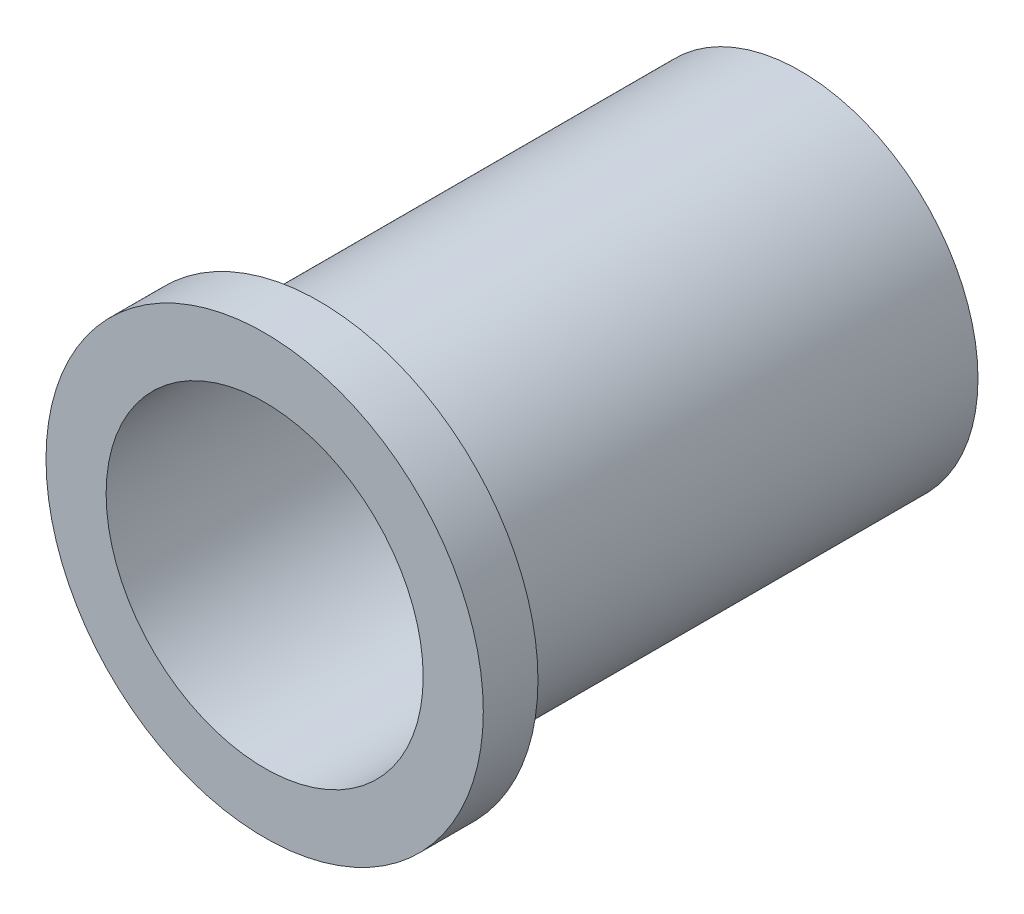
SolidWorks part; units mm, degrees
ref_plane "Front Plane" through (0, 0, 0) normal (0, 0, 1) x (1, 0, 0)
ref_plane "Top Plane" through (0, 0, 0) normal (0, 1, 0) x (1, 0, 0)
ref_plane "Right Plane" through (0, 0, 0) normal (1, 0, 0) x (0, 0, -1)
ref_plane "Plane1" through (0, 14.1965, 0) normal (0, -1, 0) x (1, 0, 0)
sketch "Sketch1" plane through (0, 14.1965, 0) normal (0, -1, 0) x (1, 0, 0)
  line L0 (13.9032, -1.7) -> (13.9032, -7)
  line L1 (13.9032, -7) -> (15.5532, -7)
  line L2 (15.5532, -7) -> (15.5532, 1.8)
  line L3 (15.5532, 1.8) -> (16.3032, 1.8)
  line L4 (16.3032, 1.8) -> (16.3032, 2.8)
  line L5 (16.3032, 2.8) -> (15.2032, 2.8)
  line L6 (15.2032, 2.8) -> (15.2032, -1.7)
  line L7 (15.2032, -1.7) -> (13.9032, -1.7)
  line L8 (12.3032, 5) -> (12.3032, -7) construction
  dimension "D1" = 12.3032
  dimension "D2" = 5
  dimension "D3" = 1.1
  dimension "D4" = 1
  dimension "D5" = 4
  dimension "D6" = 1.6
  dimension "D8" = 4.5
  dimension "D9" = 9.8
revolve "Revolve1" add sketch "Sketch1" angle 360 about L8
